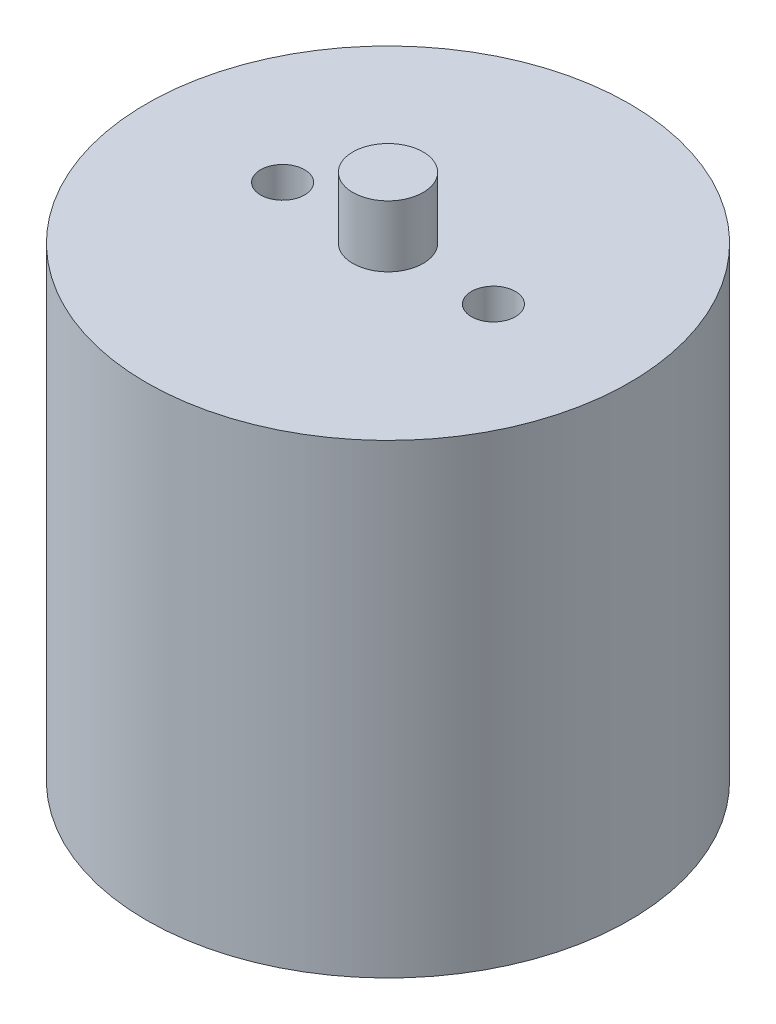
SolidWorks part; units mm, degrees
ref_plane "Front Plane" through (0, 0, 0) normal (0, 0, 1) x (1, 0, 0)
ref_plane "Top Plane" through (0, 0, 0) normal (0, 1, 0) x (1, 0, 0)
ref_plane "Right Plane" through (0, 0, 0) normal (1, 0, 0) x (0, 0, -1)
sketch "Sketch1" plane through (0, 0, 0) normal (0, 1, 0) x (1, 0, 0)
  circle A0 centre (0, 0) radius 2
ref_plane "Plane1" through (0, 2.6, 0) normal (0, 1, 0) x (1, 0, 0)
sketch "Sketch2" plane through (0, 2.6, 0) normal (0, 1, 0) x (1, 0, 0)
  circle A0 centre (0, 0) radius 13.75
extrude "Boss-Extrude1" add sketch "Sketch2" along normal blind 26.5
sketch "Sketch3" plane through (0, 29.1, 0) normal (0, 1, 0) x (1, 0, 0)
  circle A0 centre (0, 0) radius 2
  point P3 (0, 0)
extrude "Boss-Extrude2" add sketch "Sketch3" along normal blind 3.5 contours A0
sketch "Sketch4" plane through (0, 29.1, 0) normal (0, 1, 0) x (1, 0, 0)
  circle A0 centre (-6, 0) radius 1.25
  circle A1 centre (6, 0) radius 1.25
  circle A2 centre (0, 0) radius 2 construction
  point P5 (0, -4.7447)
  point P6 (-5.1313, 0)
  point P7 (0, 0)
  point P8 (5.1572, 0)
  dimension "D1" = 6
  dimension "D2" = 12
extrude "Cut-Extrude1" cut sketch "Sketch4" against normal blind 5 contours A1 | A0
extrude "Boss-Extrude3" add sketch "Sketch1" along normal up to next contours A0
sketch "Sketch5" plane through (0, 2.6, 0) normal (0, -1, 0) x (1, 0, 0)
  circle A0 centre (0, 9) radius 1.25
  circle A1 centre (0, -9) radius 1.25
  circle A2 centre (-9.5, 0) radius 1.25
  circle A3 centre (9.5, 0) radius 1.25
  circle A4 centre (0, 0) radius 2 construction
  circle A5 centre (0, 0) radius 2 construction
  point P2 (0, 6.5045)
  point P5 (0, -6.2808)
  point P8 (-7.2464, 0)
  point P11 (7.0125, 0)
  dimension "D1" = 9.5
  dimension "D2" = 19
  dimension "D3" = 9
  dimension "D4" = 18
extrude "Cut-Extrude2" cut sketch "Sketch5" against normal blind 5
